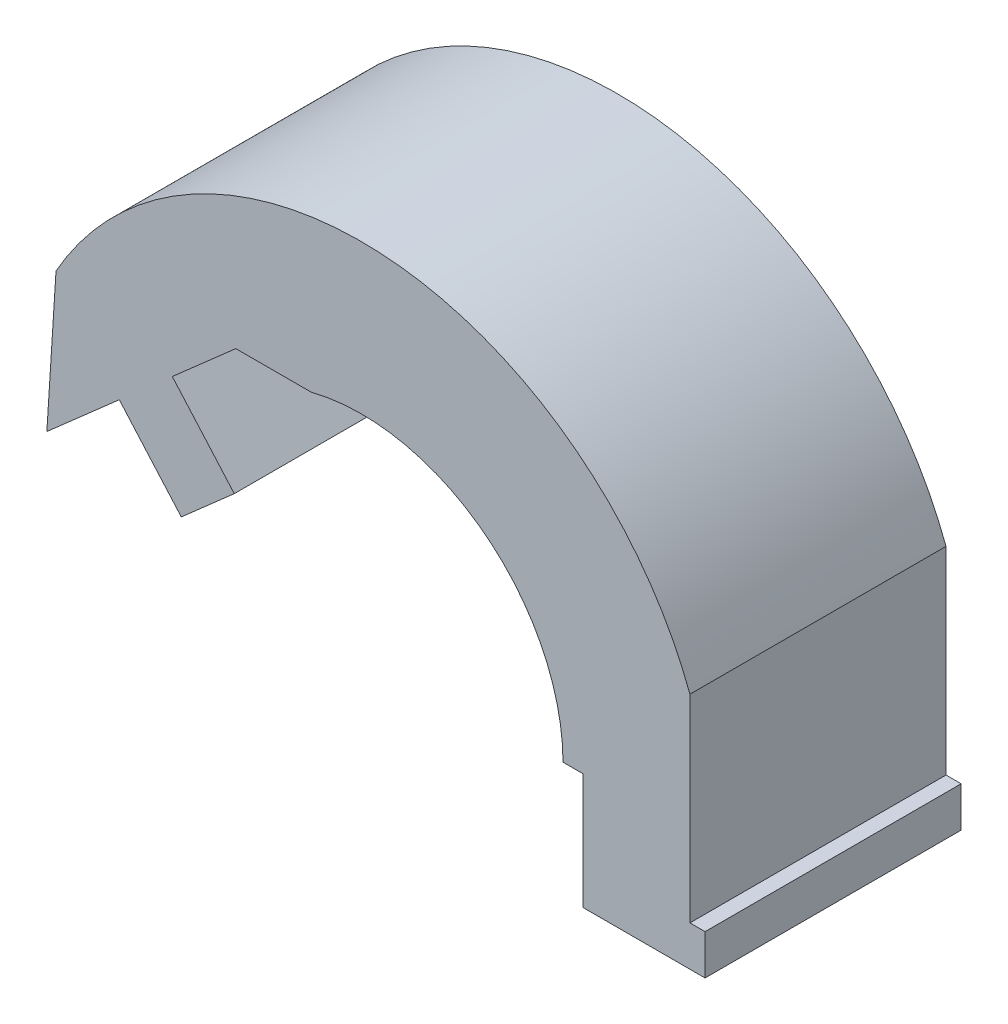
SolidWorks part; units mm, degrees
ref_plane "Front Plane" through (0, 0, 0) normal (0, 0, 1) x (1, 0, 0)
ref_plane "Top Plane" through (0, 0, 0) normal (0, 1, 0) x (1, 0, 0)
ref_plane "Right Plane" through (0, 0, 0) normal (1, 0, 0) x (0, 0, -1)
sketch "Sketch3" plane through (0, 0, 0) normal (0, 0, 1) x (1, 0, 0)
  line L0 (-39.9085, 10.7577) -> (-40.0991, 10.5899)
  line L3 (-37.0887, 13.2392) -> (-37.2794, 13.0714)
  line L8 (-43.4994, 7.5974) -> (-40.0991, 10.5899) construction
  line L17 (-17.1709, 0.1948) -> (-17.1709, 6.1948) construction
  line L36 (-34.1292, 15.8438) -> (-30.3792, 15.8438) construction
  line L37 (-37.0887, 13.2392) -> (-33.845, 9.5535) construction
  line L39 (-43.4994, 7.5974) -> (-43.0448, 14.7233)
  line L51 (-17.1709, 0.1948) -> (-11.4125, 0.1948) construction
  line L52 (-11.3528, 5.1546) -> (-11.3528, 2.6948) construction
  line L57 (-33.845, 9.5535) -> (-36.8555, 6.9042) construction
  line L58 (-11.4125, 0.1948) -> (-10.6028, 0.1948) construction
  line L60 (-11.3528, 2.6948) -> (-10.6028, 2.6948) construction
  line L61 (-10.6028, 0.1948) -> (-10.6028, 2.6948) construction
  line L62 (-36.8555, 6.9042) -> (-40.0991, 10.5899) construction
  line L63 (-37.0887, 13.2392) -> (-34.1292, 15.8438) construction
  line L64 (-11.6068, 5.1546) -> (-11.6068, 2.4408)
  line L65 (-11.6068, 2.4408) -> (-10.8568, 2.4408)
  line L66 (-10.8568, 2.4408) -> (-10.8568, 0.4488)
  line L67 (-10.8568, 0.4488) -> (-16.9169, 0.4488)
  line L68 (-16.9169, 0.4488) -> (-16.9169, 6.1948)
  line L69 (-37.2794, 13.0714) -> (-34.2035, 9.5764)
  line L70 (-34.2035, 9.5764) -> (-36.8326, 7.2626)
  line L71 (-36.8326, 7.2626) -> (-39.9085, 10.7577)
  line L72 (-11.6068, 5.1546) -> (-11.6068, 12.2623)
  line L73 (-17.9002, 6.1948) -> (-16.9169, 6.1948)
  line L82 (-37.0887, 13.2392) -> (-33.845, 9.5535)
  line L83 (-33.845, 9.5535) -> (-36.8555, 6.9042)
  line L84 (-36.8555, 6.9042) -> (-40.0991, 10.5899)
  line L85 (-40.0991, 10.5899) -> (-43.4994, 7.5974)
  line L86 (-16.5246, -6.5052) -> (-0.3986, -6.5052)
  line L87 (-0.3986, -6.5052) -> (-0.3986, 6.1948)
  line L88 (-0.3986, 6.1948) -> (-11.3528, 6.1948)
  line L89 (-11.3528, 6.1948) -> (-11.3528, 2.6948)
  line L90 (-11.3528, 2.6948) -> (-10.6028, 2.6948)
  line L91 (-10.6028, 2.6948) -> (-10.6028, 0.1948)
  line L92 (-10.6028, 0.1948) -> (-17.1709, 0.1948)
  line L93 (-17.1709, 0.1948) -> (-17.1709, 6.1948)
  line L94 (-17.1709, 6.1948) -> (-18.6296, 6.1948)
  line L95 (-18.6296, 6.1948) -> (-24.3165, -3.6552)
  line L96 (-36.4408, 3.3448) -> (-30.3792, 13.8438)
  line L97 (-30.3792, 13.8438) -> (-30.3792, 15.8438)
  line L98 (-30.3792, 15.8438) -> (-34.1292, 15.8438)
  line L99 (-34.1292, 15.8438) -> (-37.0887, 13.2392)
  line L100 (-37.0887, 13.2392) -> (-33.845, 9.5535) construction
  line L101 (-33.845, 9.5535) -> (-36.8555, 6.9042) construction
  line L102 (-36.8555, 6.9042) -> (-40.0991, 10.5899) construction
  line L103 (-40.0991, 10.5899) -> (-43.4994, 7.5974)
  line L104 (-16.5246, -6.5052) -> (-0.3986, -6.5052) construction
  line L105 (-0.3986, -6.5052) -> (-0.3986, 6.1948) construction
  line L106 (-0.3986, 6.1948) -> (-11.3528, 6.1948) construction
  line L107 (-11.3528, 6.1948) -> (-11.3528, 2.6948) construction
  line L108 (-11.3528, 2.6948) -> (-10.6028, 2.6948) construction
  line L109 (-10.6028, 2.6948) -> (-10.6028, 0.1948) construction
  line L110 (-10.6028, 0.1948) -> (-17.1709, 0.1948) construction
  line L111 (-17.1709, 0.1948) -> (-17.1709, 6.1948) construction
  line L112 (-17.1709, 6.1948) -> (-18.6296, 6.1948) construction
  line L113 (-18.6296, 6.1948) -> (-24.3165, -3.6552) construction
  line L114 (-36.4408, 3.3448) -> (-30.3792, 13.8438) construction
  line L115 (-30.3792, 13.8438) -> (-30.3792, 15.8438) construction
  line L116 (-30.3792, 15.8438) -> (-34.1292, 15.8438)
  line L117 (-34.1292, 15.8438) -> (-37.0887, 13.2392)
  arc A2 (-30.3792, 15.8438) -> (-17.9002, 6.1948) centre (-27.9002, 6.156) cw
  arc A9 (-11.6068, 12.2623) -> (-43.0448, 14.7233) centre (-27.9002, 6.156) ccw
  arc A11 (-43.4994, 7.5974) -> (-16.5246, -6.5052) centre (-30.3786, -0.1552) ccw
  arc A12 (-36.4408, 3.3448) -> (-24.3165, -3.6552) centre (-30.3786, -0.1552) ccw
  arc A13 (-43.4994, 7.5974) -> (-16.5246, -6.5052) centre (-30.3786, -0.1552) ccw construction
  arc A14 (-36.4408, 3.3448) -> (-24.3165, -3.6552) centre (-30.3786, -0.1552) ccw construction
  dimension "D2" = 0
  dimension "D3" = 10
  dimension "D4" = 7.4
  dimension "D1" = 0.254
  dimension "D5" = 45
extrude "Boss-Extrude1" add sketch "Sketch3" against normal blind 12.7
